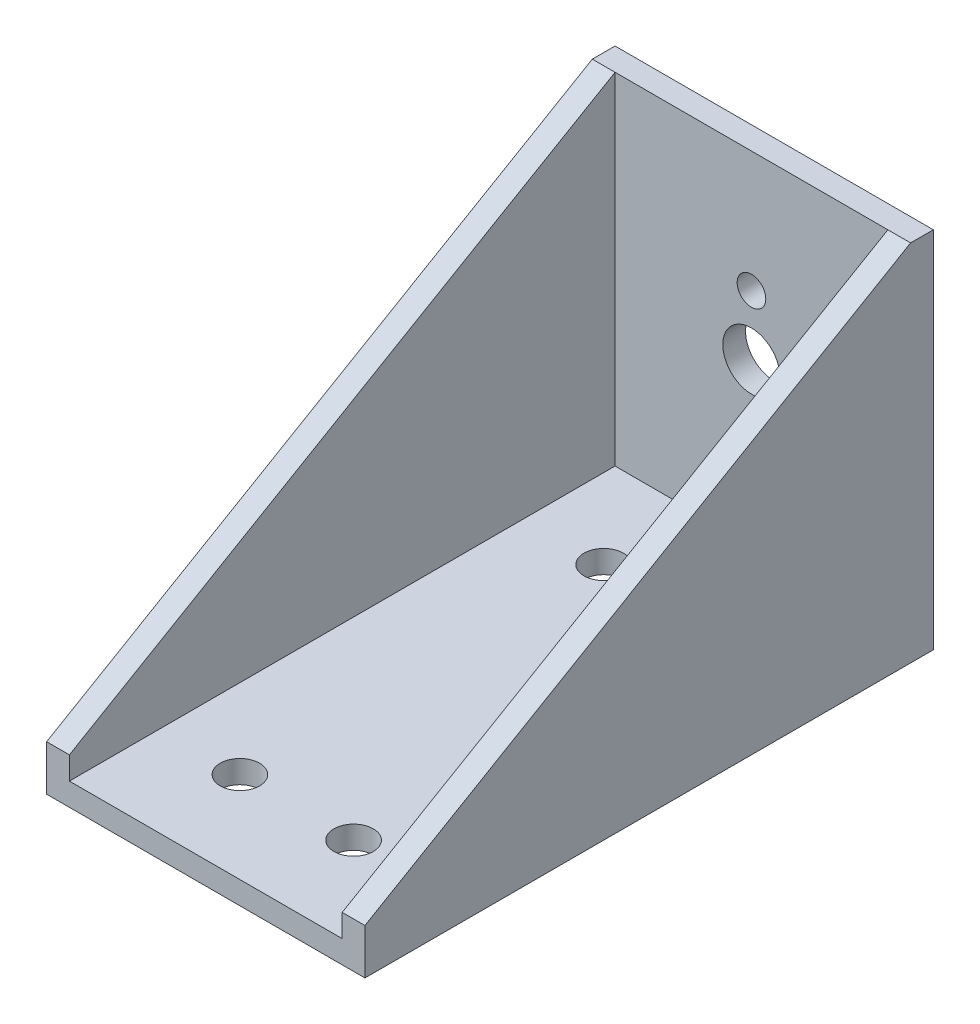
SolidWorks part; units mm, degrees
ref_plane "Front Plane" through (0, 0, 0) normal (0, 0, 1) x (1, 0, 0)
ref_plane "Top Plane" through (0, 0, 0) normal (0, 1, 0) x (1, 0, 0)
ref_plane "Right Plane" through (0, 0, 0) normal (1, 0, 0) x (0, 0, -1)
sketch "Sketch1" plane through (0, 0, 0) normal (0, 0, 1) x (1, 0, 0)
  line L0 (0, 0) -> (0, 8.5) construction
  line L1 (-22.225, -25.4) -> (22.225, -25.4)
  line L2 (-22.225, -25.4) -> (-22.225, 25.4)
  line L3 (-22.225, 25.4) -> (22.225, 25.4)
  line L4 (22.225, -25.4) -> (22.225, 25.4)
  line L5 (-22.225, -25.4) -> (22.225, 25.4) construction
  line L6 (-22.225, 25.4) -> (22.225, -25.4) construction
  line L7 (0, 0) -> (-8.9164, 0) construction
  line L9 (0, -2) -> (-9.9169, -2) construction
  circle A0 centre (0, 8.5) radius 2
  circle A1 centre (0, -8.5) radius 2
  circle A3 centre (0, 0) radius 4
  point P0 (0, 0)
  point P16 (0, 1.5)
  dimension "D4" = 4
  dimension "D5" = 8
  dimension "D1" = 44.45
  dimension "D2" = 50.8
  dimension "D3" = 8.5
extrude "Boss-Extrude1" add sketch "Sketch1" along normal blind 3.175
sketch "Sketch3" plane through (0, 0, 3.175) normal (0, 0, 1) x (1, 0, 0)
  line L0 (22.225, -25.4) -> (22.225, 25.4) construction
  line L1 (-22.225, -25.4) -> (22.225, -25.4)
  line L2 (-22.225, -25.4) -> (-22.225, -22.225)
  line L3 (-22.225, -22.225) -> (22.225, -22.225)
  line L4 (22.225, -25.4) -> (22.225, -22.225)
  dimension "D1" = 3.175
extrude "Boss-Extrude2" add sketch "Sketch3" along normal blind 76.2
sketch "Sketch6" plane through (0, -22.225, 0) normal (0, 1, 0) x (1, 0, 0)
  line L2 (22.225, -79.375) -> (-22.225, -79.375) construction
  line L7 (0, -79.375) -> (0, -100.6852) construction
  line L11 (22.225, -79.375) -> (19.05, -79.375)
  line L12 (-22.225, -3.175) -> (-19.05, -3.175)
  line L13 (-22.225, -3.175) -> (-22.225, -79.375)
  line L14 (-22.225, -79.375) -> (-19.05, -79.375)
  line L15 (-19.05, -3.175) -> (-19.05, -79.375)
  line L16 (22.225, -3.175) -> (19.05, -3.175)
  line L17 (22.225, -3.175) -> (22.225, -79.375)
  line L18 (19.05, -3.175) -> (19.05, -79.375)
  dimension "D1" = 3.175
extrude "Boss-Extrude3" add sketch "Sketch6" along normal up to vertex (47.625 mm away) up to point (-22.225, 25.4, 0)
chamfer "Chamfer1" distance 44.45 distance2 76.2 2 edges at (-20.6375, 25.4, 79.375) (20.6375, 25.4, 79.375)
sketch "Sketch7" plane through (0, 0, 3.175) normal (0, 0, 1) x (1, 0, 0)
  circle A0 centre (0, 0) radius 12.5 construction
  dimension "D1" = 25
sketch "Sketch8" plane through (0, -22.225, 0) normal (0, 1, 0) x (1, 0, 0)
  line L0 (0, -3.175) -> (0, -79.375) construction
  line L1 (-12.5, -3.175) -> (12.5, -3.175) construction
  line L2 (19.05, -79.375) -> (-19.05, -79.375) construction
  line L4 (-7.9375, -66.675) -> (7.9375, -66.675) construction
  line L5 (-7.9375, -66.675) -> (-7.9375, -15.875) construction
  line L6 (-7.9375, -15.875) -> (7.9375, -15.875) construction
  line L7 (7.9375, -66.675) -> (7.9375, -15.875) construction
  line L8 (-7.9375, -66.675) -> (7.9375, -15.875) construction
  line L9 (-7.9375, -15.875) -> (7.9375, -66.675) construction
  circle A0 centre (-7.9375, -15.875) radius 2.75
  circle A1 centre (7.9375, -15.875) radius 2.75
  circle A2 centre (7.9375, -66.675) radius 2.75
  circle A3 centre (-7.9375, -66.675) radius 2.75
  point P6 (0, -41.275)
  dimension "D3" = 5.5
  dimension "D1" = 50.8
  dimension "D2" = 15.875
extrude "Cut-Extrude1" cut sketch "Sketch8" against normal through all
